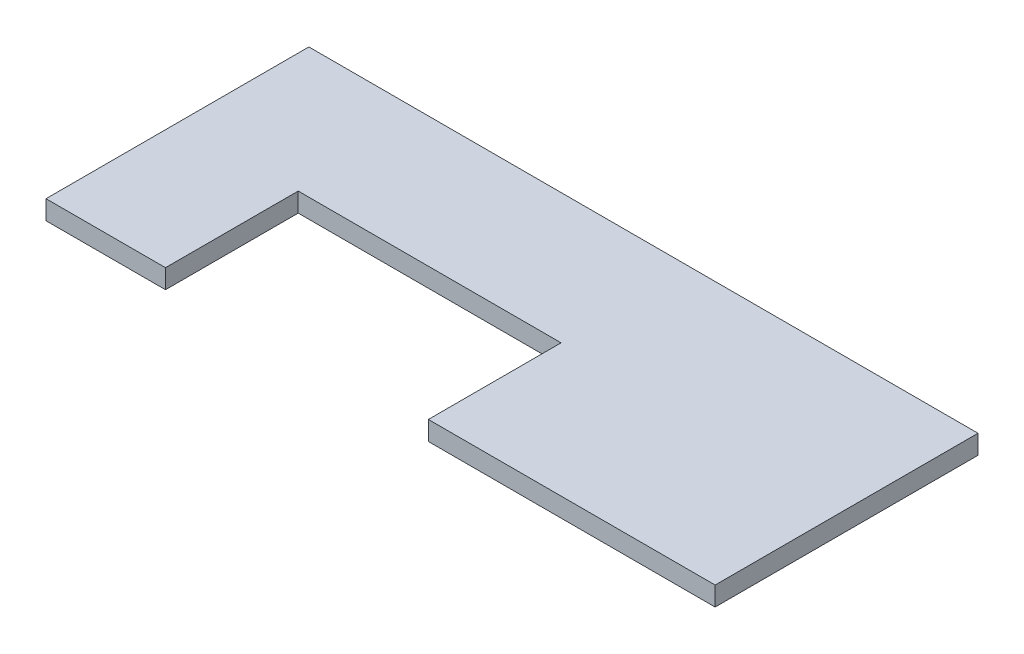
SolidWorks part; units mm, degrees
ref_plane "Front Plane" through (0, 0, 0) normal (0, 0, 1) x (1, 0, 0)
ref_plane "Top Plane" through (0, 0, 0) normal (0, 1, 0) x (1, 0, 0)
ref_plane "Right Plane" through (0, 0, 0) normal (1, 0, 0) x (0, 0, -1)
sketch "Sketch2" plane through (0, 0, 0) normal (0, 1, 0) x (1, 0, 0)
  line L0 (-196.2397, 90.2893) -> (-56.2397, 90.2893)
  line L1 (-56.2397, 90.2893) -> (-56.2397, 35.2893)
  line L2 (-56.2397, 35.2893) -> (-116.2397, 35.2893)
  line L3 (-116.2397, 35.2893) -> (-116.2397, 63.0579)
  line L4 (-116.2397, 63.0579) -> (-171.2397, 63.0579)
  line L5 (-171.2397, 63.0579) -> (-171.2397, 35.2893)
  line L6 (-171.2397, 35.2893) -> (-196.2397, 35.2893)
  line L7 (-196.2397, 35.2893) -> (-196.2397, 90.2893)
  dimension "D1" = 140
  dimension "D2" = 55
  dimension "D3" = 25
  dimension "D4" = 55
  dimension "D5" = 60
  dimension "D6" = 55
extrude "Boss-Extrude1" add sketch "Sketch2" along normal blind 4
